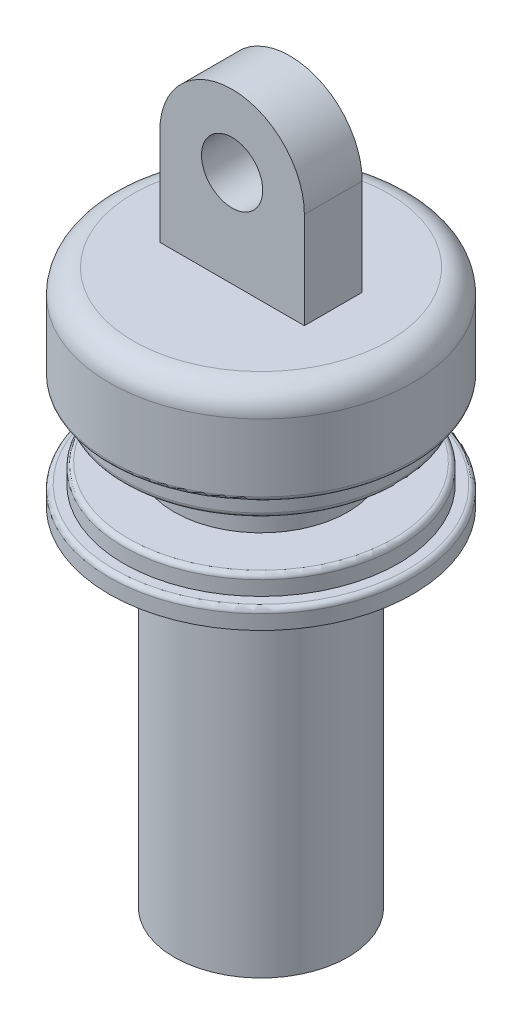
SolidWorks part; units mm, degrees
ref_plane "Front Plane" through (0, 0, 0) normal (0, 0, 1) x (1, 0, 0)
ref_plane "Top Plane" through (0, 0, 0) normal (0, 1, 0) x (1, 0, 0)
ref_plane "Right Plane" through (0, 0, 0) normal (1, 0, 0) x (0, 0, -1)
sketch "Sketch1" plane through (0, 0, 0) normal (0, 0, 1) x (1, 0, 0)
  line L0 (-15, 0) -> (15, 0) construction
  line L1 (-15, -20) -> (15, -20)
  line L2 (-15, -20) -> (-15, 0)
  line L4 (15, -20) -> (15, 0)
  arc A0 (-15, 0) -> (15, 0) centre (0, 0) cw
  point P6 (-90.3665, -20.1345)
  dimension "D1" = 30
  dimension "D3" = 20
  dimension "D4" = 15
extrude "Boss-Extrude1" add sketch "Sketch1" along normal mid plane 12
sketch "Sketch2" plane through (0, -20, 0) normal (0, -1, 0) x (1, 0, 0)
  circle A0 centre (0, 0) radius 31.5
  dimension "D1" = 63
extrude "Boss-Extrude2" add sketch "Sketch2" along normal blind 20
sketch "Sketch3" plane through (0, -40, 0) normal (0, -1, 0) x (1, 0, 0)
  circle A0 centre (0, 0) radius 28.5
  circle A1 centre (0, 0) radius 31.5 construction
  dimension "D1" = 3
extrude "Boss-Extrude3" add sketch "Sketch3" along normal blind 5
fillet "Fillet1" radius 5 1 edges at (0, -20, -31.5)
fillet "Fillet2" radius 1 3 edges at (0, -45, -28.5) (0, -40, -28.5) (0, -40, -31.5)
sketch "Sketch4" plane through (0, 0, 6) normal (0, 0, 1) x (1, 0, 0)
  circle A0 centre (0, 0) radius 6.35
  dimension "D1" = 12.7
extrude "Cut-Extrude1" cut sketch "Sketch4" against normal blind 13
sketch "Sketch5" plane through (0, -45, 0) normal (0, -1, 0) x (1, 0, 0)
  circle A0 centre (0, 0) radius 18
  dimension "D1" = 36
extrude "Boss-Extrude4" add sketch "Sketch5" along normal blind 90
sketch "Sketch7" plane through (0, 0, 0) normal (1, 0, 0) x (0, 0, -1)
  line L0 (0, 0) -> (0, -162.1773) construction
  line L1 (0, -135) -> (-6, -135)
  line L2 (-18, -135) -> (18, -135) construction
  line L3 (-6, -135) -> (-6, -130)
  line L4 (-6, -130) -> (-13, -130)
  line L5 (-13, -130) -> (-13, -49)
  line L6 (-13, -49) -> (0, -49)
  line L7 (0, -49) -> (0, -135)
  line L8 (-18, -45) -> (-18, -135) construction
  line L9 (28.5, -44) -> (-28.5, -44) construction
  dimension "D1" = 6
  dimension "D2" = 5
  dimension "D3" = 5
  dimension "D4" = 5
revolve "Cut-Revolve1" cut sketch "Sketch7" angle 360 about L0
sketch "Sketch8" plane through (0, 0, 0) normal (1, 0, 0) x (0, 0, -1)
  line L0 (-18, -55) -> (-27.5, -55)
  line L1 (-18, -45) -> (-18, -135) construction
  line L2 (-28.5, -56) -> (-28.5, -59)
  line L3 (-28.5, -59) -> (-30.5, -59)
  line L4 (-31.5, -60) -> (-31.5, -63)
  line L5 (-31.5, -63) -> (-18, -63)
  line L6 (-18, -63) -> (-18, -55)
  line L7 (-28.5, -41) -> (-28.5, -44) construction
  line L8 (-31.5, -25) -> (-31.5, -39) construction
  line L9 (-18, -45) -> (18, -45) construction
  line L10 (0, -49.5667) -> (0, -70.7029) construction
  arc A0 (-27.5, -55) -> (-28.5, -56) centre (-27.5, -56) ccw
  arc A1 (-30.5, -59) -> (-31.5, -60) centre (-30.5, -60) ccw
  point P16 (-28.5, -55)
  point P19 (-31.5, -59)
  dimension "D5" = 1
  dimension "D1" = 10
  dimension "D2" = 8
  dimension "D3" = 4
  dimension "D4" = 3
revolve "Revolve1" add sketch "Sketch8" angle 360 about L10
